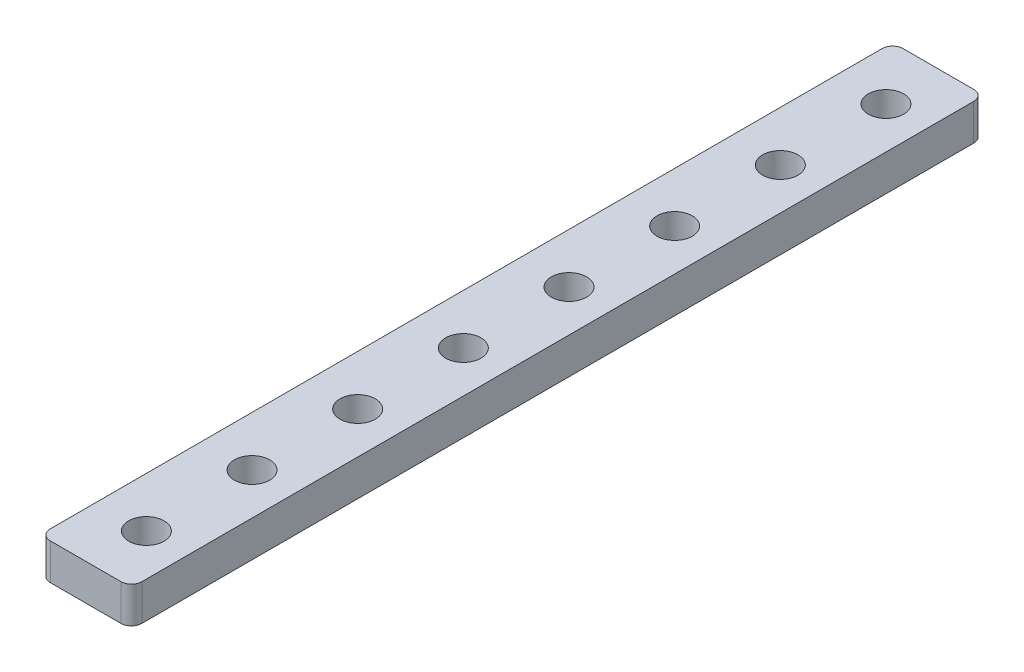
SolidWorks part; units mm, degrees
ref_plane "Front Plane" through (0, 0, 0) normal (0, 0, 1) x (1, 0, 0)
ref_plane "Top Plane" through (0, 0, 0) normal (0, 1, 0) x (1, 0, 0)
ref_plane "Right Plane" through (0, 0, 0) normal (1, 0, 0) x (0, 0, -1)
sketch "Sketch1" plane through (0, 0, 0) normal (0, 1, 0) x (1, 0, 0)
  line L1 (-12, 102.5) -> (10, 102.5)
  line L2 (-12, 102.5) -> (-12, -102.5)
  line L3 (-12, -102.5) -> (10, -102.5)
  line L4 (10, 102.5) -> (10, -102.5)
  line L5 (0, -102.5) -> (0, 102.5) construction
  line L6 (-12, 0) -> (10, 0) construction
  point P0 (0, 0)
  point P4 (0, -88.9)
  dimension "D1" = 12
  dimension "D2" = 205
  dimension "D3" = 13.6
  dimension "D4" = 10
sketch "Sketch2" plane through (0, 0, 0) normal (0, 1, 0) x (1, 0, 0)
  point P0 (0, -88.9)
extrude "Boss-Extrude1" add sketch "Sketch1" along normal blind 8.7
hole_wizard "M8 Clearance Hole1" positions "Sketch2" profile "Sketch3" hole size "M8" standard "ISO" end condition up to next
sketch "Sketch3" plane through (0, 0, 88.9) normal (1, 0, 0) x (0, 0, -1)
  line L0 (0, 0) -> (0, 8.7)
  line L1 (0, 8.7) -> (4.25, 8.7)
  line L2 (4.25, 8.7) -> (4.25, 0)
  line L5 (4.25, 0) -> (0, 0)
  line L11 (0, -6.35) -> (0, 107.95) construction
  dimension "Thru Hole Dia." = 8.5
  dimension "Thru Hole Depth" = 8.7
pattern_linear "LPattern1" count 8 spacing 25.4 along (0, 0, -1) of "M8 Clearance Hole1"
fillet "Fillet1" radius 2.5 4 edges at (10, 4.35, 102.5) (-12, 4.35, -102.5) (10, 4.35, -102.5) (-12, 4.35, 102.5)
